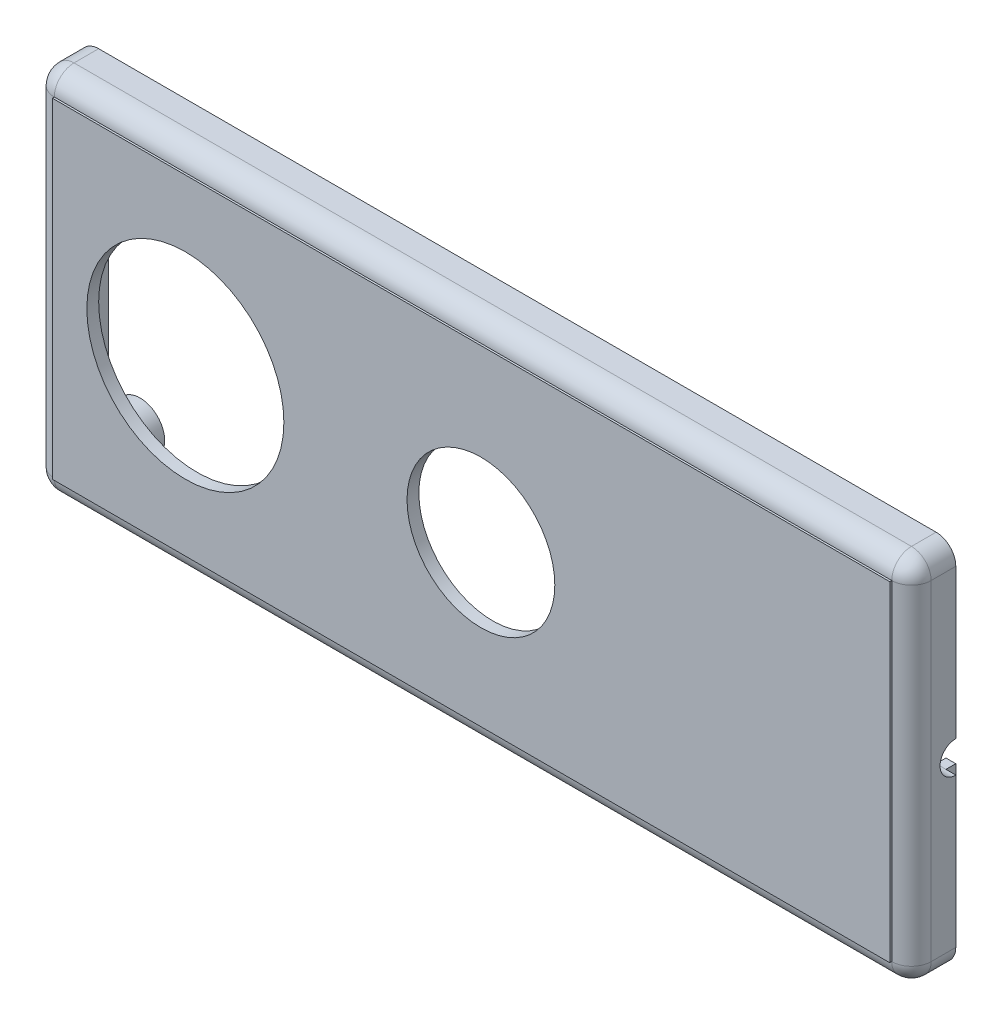
SolidWorks part; units mm, degrees
ref_plane "前视基准面" through (0, 0, 0) normal (0, 0, 1) x (1, 0, 0)
ref_plane "上视基准面" through (0, 0, 0) normal (0, 1, 0) x (1, 0, 0)
ref_plane "右视基准面" through (0, 0, 0) normal (1, 0, 0) x (0, 0, -1)
sketch "草图1" plane through (0, 0, 0) normal (0, 0, 1) x (1, 0, 0)
  line L1 (-44.5, 18.75) -> (44.5, 18.75)
  line L2 (-44.5, 18.75) -> (-44.5, -18.75)
  line L3 (-44.5, -18.75) -> (44.5, -18.75)
  line L4 (44.5, 18.75) -> (44.5, -18.75)
  line L5 (-44.5, 18.75) -> (44.5, -18.75) construction
  line L6 (-44.5, -18.75) -> (44.5, 18.75) construction
  point P0 (0, 0)
  dimension "D1" = 89
  dimension "D2" = 37.5
extrude "凸台-拉伸1" add sketch "草图1" along normal blind 4.5
sketch "草图2" plane through (0, 0, 0) normal (0, 0, -1) x (-1, 0, 0)
  line L0 (-44.5, 18.75) -> (44.5, 18.75) construction
  line L1 (-42.5, 16.75) -> (42.5, 16.75)
  line L2 (-42.5, 16.75) -> (-42.5, -16.75)
  line L3 (-42.5, -16.75) -> (42.5, -16.75)
  line L4 (42.5, 16.75) -> (42.5, -16.75)
  line L5 (44.5, -18.75) -> (-44.5, -18.75) construction
  line L6 (-44.5, -18.75) -> (-44.5, 18.75) construction
  line L7 (44.5, 18.75) -> (44.5, -18.75) construction
  dimension "D1" = 2
  dimension "D2" = 2
  dimension "D3" = 2
  dimension "D4" = 2
extrude "切除-拉伸1" cut sketch "草图2" against normal blind 3.5
sketch "草图3" plane through (44.5, 0, 0) normal (1, 0, 0) x (0, 0, -1)
  line L0 (0, -18.75) -> (0, 18.75) construction
  line L1 (0, 1.6) -> (0, -1.6)
  arc A0 (0, -1.6) -> (0, 1.6) centre (0, 0) cw
  dimension "D1" = 1.6
extrude "切除-拉伸3" cut sketch "草图3" against normal blind 4
fillet "圆角1" radius 2 12 edges at (0, -18.75, 4.5) (-44.5, 0, 4.5) (0, 18.75, 4.5) (44.5, 0, 4.5) (-44.5, 18.75, 2.25) (-44.5, -18.75, 2.25) (44.5, -18.75, 2.25) (44.5, 18.75, 2.25) (42.5, -16.75, 1.75) (42.5, 16.75, 1.75) (-42.5, 16.75, 1.75) (-42.5, -16.75, 1.75)
sketch "草图9" plane through (0, 0, 0) normal (0, 0, -1) x (-1, 0, 0)
  line L10 (42.5, -14.75) -> (42.5, 14.75) construction
  line L20 (40.5, 16.75) -> (-40.5, 16.75) construction
  line L21 (-40.5, -16.75) -> (40.5, -16.75) construction
  line L26 (-41.5, 17.75) -> (41.5, 17.75)
  line L28 (-41.5, -17.75) -> (41.5, -17.75)
  line L29 (43.5, 15.75) -> (43.5, -15.75)
  line L30 (-43.5, 1.6) -> (-42.5, 1.6)
  line L35 (-40.5, 16.75) -> (40.5, 16.75)
  line L37 (-40.5, -16.75) -> (40.5, -16.75)
  line L38 (42.5, 14.75) -> (42.5, -14.75)
  line L39 (-42.5, 1.6) -> (-44.5, 1.6) construction
  line L40 (-42.5, -1.6) -> (-43.5, -1.6)
  line L41 (-42.5, -1.6) -> (-44.5, -1.6) construction
  line L42 (-43.5, 15.75) -> (-43.5, 1.6)
  line L43 (-43.5, -1.6) -> (-43.5, -15.75)
  line L44 (-42.5, 14.75) -> (-42.5, 1.6)
  line L45 (-42.5, -1.6) -> (-42.5, -14.75)
  arc A0 (-43.5, -15.75) -> (-41.5, -17.75) centre (-41.5, -15.75) ccw
  arc A1 (-41.5, 17.75) -> (-43.5, 15.75) centre (-41.5, 15.75) ccw
  arc A2 (41.5, 17.75) -> (43.5, 15.75) centre (41.5, 15.75) cw
  arc A3 (41.5, -17.75) -> (43.5, -15.75) centre (41.5, -15.75) ccw
  arc A4 (-40.5, 16.75) -> (-42.5, 14.75) centre (-40.5, 14.75) ccw
  arc A5 (-42.5, -14.75) -> (-40.5, -16.75) centre (-40.5, -14.75) ccw
  arc A6 (40.5, 16.75) -> (42.5, 14.75) centre (40.5, 14.75) cw
  arc A7 (40.5, -16.75) -> (42.5, -14.75) centre (40.5, -14.75) ccw
  point P64 (42.5, -16.75)
  dimension "D20" = 2
  dimension "D21" = 2
  dimension "D22" = 2
  dimension "D23" = 2
  dimension "D26" = 2
  dimension "D27" = 2
  dimension "D28" = 2
  dimension "D29" = 2
  dimension "D17" = 1
  dimension "D18" = 1
  dimension "D19" = 1
  dimension "D25" = 1
extrude "凸台-拉伸2" add sketch "草图9" along normal blind 1
sketch "草图10" plane through (0, 0, 3.5) normal (0, 0, -1) x (-1, 0, 0)
  line L0 (42.5, -14.75) -> (42.5, 14.75) construction
  line L1 (-40.5, -16.75) -> (40.5, -16.75) construction
  line L2 (40.5, 16.75) -> (-40.5, 16.75) construction
  line L5 (-42.5, 14.75) -> (-42.5, -14.75) construction
  line L6 (40.5, -16.75) -> (-40.5, -16.75) construction
  circle A0 centre (39.3, -13.35) radius 2.5
  circle A1 centre (39.3, 13.35) radius 2.5
  circle A2 centre (-34.5, 13.35) radius 2.5
  circle A3 centre (-34.5, -13.35) radius 2.5
  dimension "D1" = 5
  dimension "D2" = 3.2
  dimension "D3" = 3.4
  dimension "D4" = 3.2
  dimension "D5" = 5
  dimension "D6" = 3.4
  dimension "D7" = 5
  dimension "D8" = 3.4
  dimension "D9" = 8
  dimension "D10" = 5
  dimension "D11" = 3.4
  dimension "D12" = 8
extrude "凸台-拉伸3" add sketch "草图10" along normal blind 4.5
sketch "草图11" plane through (0, 0, -1) normal (0, 0, -1) x (-1, 0, 0)
  circle A0 centre (-34.5, 13.35) radius 0.79
  circle A1 centre (-34.5, -13.35) radius 0.79
  circle A2 centre (39.3, 13.35) radius 0.79
  circle A3 centre (39.3, -13.35) radius 0.79
  dimension "D1" = 1.58
  dimension "D2" = 1.58
  dimension "D3" = 1.58
  dimension "D4" = 1.58
extrude "切除-拉伸9" cut sketch "草图11" against normal blind 3
sketch "草图12" plane through (0, 0, 4.5) normal (0, 0, 1) x (1, 0, 0)
  line L1 (-42.5, 16.75) -> (42.5, 16.75)
  line L2 (-42.5, 16.75) -> (-42.5, -16.75)
  line L3 (-42.5, -16.75) -> (42.5, -16.75)
  line L4 (42.5, 16.75) -> (42.5, -16.75)
extrude "凸台-拉伸4" add sketch "草图12" along normal blind 0.2
sketch "草图8" plane through (0, 0, 3.5) normal (0, 0, -1) x (-1, 0, 0)
  line L1 (-40.5, -16.75) -> (40.5, -16.75) construction
  line L2 (42.5, -14.75) -> (42.5, 14.75) construction
  circle A0 centre (-1, -0.55) radius 7.5
  dimension "D1" = 15
  dimension "D2" = 16.2
  dimension "D3" = 43.5
extrude "切除-拉伸8" cut sketch "草图8" against normal blind 3
sketch "草图7" plane through (0, 0, 3.5) normal (0, 0, -1) x (-1, 0, 0)
  line L0 (40.5, -16.75) -> (-40.5, -16.75) construction
  line L1 (42.5, -14.75) -> (42.5, 14.75) construction
  circle A0 centre (29, 0) radius 10
  dimension "D1" = 20
  dimension "D2" = 13.5
  dimension "D3" = 16.75
extrude "切除-拉伸7" cut sketch "草图7" against normal blind 3
sketch "草图15" plane through (0, 0, -1) normal (0, 0, -1) x (-1, 0, 0)
  line L0 (44.5, 16.75) -> (44.5, -16.75) construction
  line L3 (-27.5, -18.75) -> (-14.5, -18.75)
  line L5 (42.5, -18.75) -> (-42.5, -18.75) construction
  line L9 (-27.5, -18.75) -> (-28.5, -16.75)
  line L10 (40.5, -16.75) -> (-40.5, -16.75) construction
  line L11 (-28.5, -16.75) -> (-13.5, -16.75)
  line L12 (-13.5, -16.75) -> (-14.5, -18.75)
  dimension "D1" = 15
  dimension "D2" = 13
  dimension "D3" = 1
  dimension "D4" = 59
extrude "切除-拉伸12" cut sketch "草图15" against normal blind 3.8
